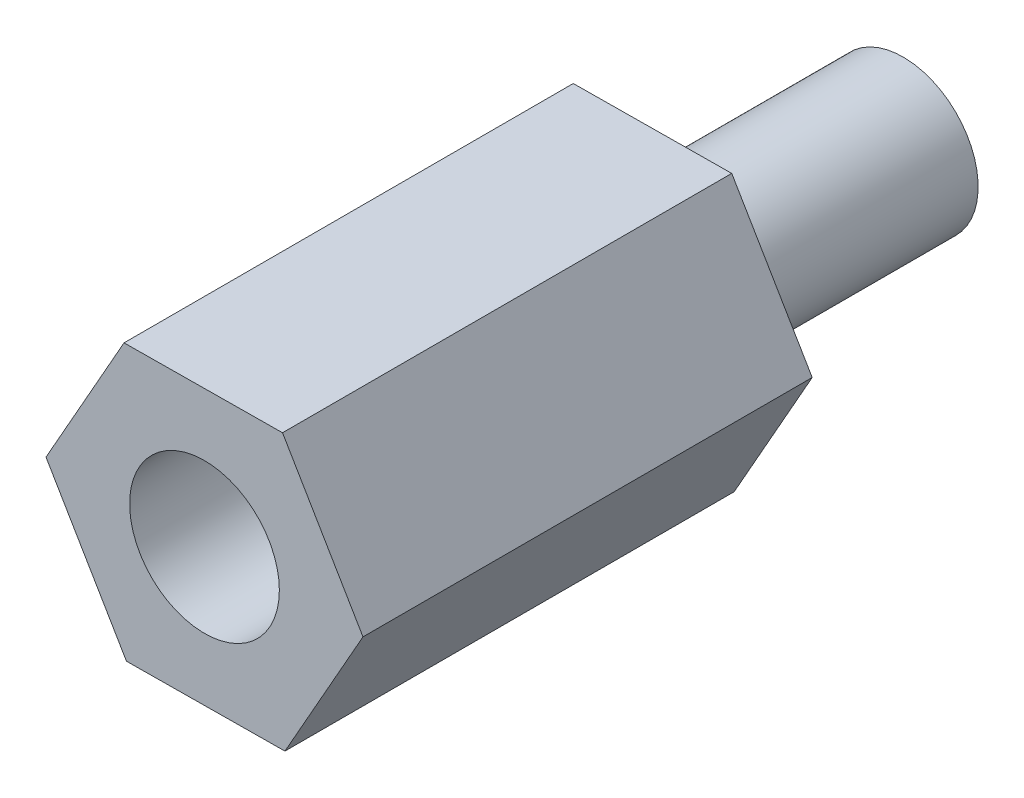
SolidWorks part; units mm, degrees
ref_plane "前视基准面" through (0, 0, 0) normal (0, 0, 1) x (1, 0, 0)
ref_plane "上视基准面" through (0, 0, 0) normal (0, 1, 0) x (1, 0, 0)
ref_plane "右视基准面" through (0, 0, 0) normal (1, 0, 0) x (0, 0, -1)
sketch "草图1" plane through (0, 0, 0) normal (0, 0, 1) x (1, 0, 0)
  line L1 (1.6119, -2.7359) -> (3.1753, 0.028)
  line L2 (3.1753, 0.028) -> (1.5634, 2.7639)
  line L3 (1.5634, 2.7639) -> (-1.6119, 2.7359)
  line L4 (-1.6119, 2.7359) -> (-3.1753, -0.028)
  line L5 (-3.1753, -0.028) -> (-1.5634, -2.7639)
  line L6 (-1.5634, -2.7639) -> (1.6119, -2.7359)
  circle A0 centre (0, 0) radius 2.75 construction
  circle A1 centre (0, 0) radius 1.5
extrude "凸台-拉伸1" add sketch "草图1" along normal blind 9
sketch "草图2" plane through (0, 0, 0) normal (0, 0, -1) x (-1, 0, 0)
  circle A0 centre (0, 0) radius 1.5
extrude "凸台-拉伸2" add sketch "草图2" along normal blind 5 separate body
